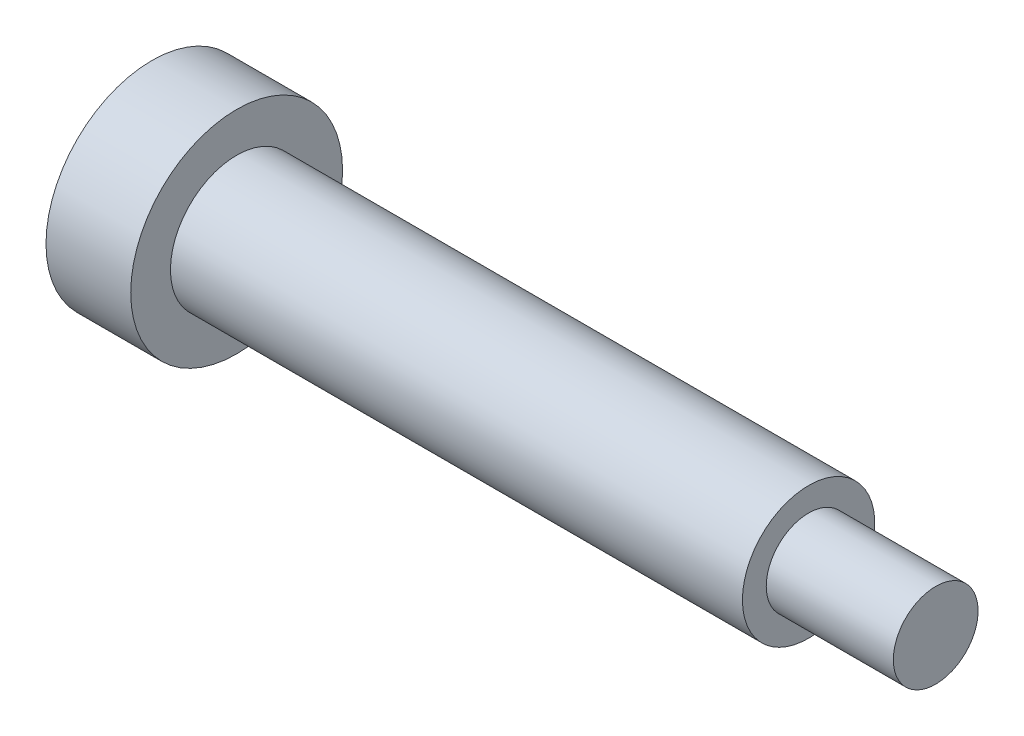
SolidWorks part; units mm, degrees
ref_plane "Front Plane" through (0, 0, 0) normal (0, 0, 1) x (1, 0, 0)
ref_plane "Top Plane" through (0, 0, 0) normal (0, 1, 0) x (1, 0, 0)
ref_plane "Right Plane" through (0, 0, 0) normal (1, 0, 0) x (0, 0, -1)
sketch "Sketch1" plane through (0, 0, 0) normal (0, 0, 1) x (1, 0, 0)
  line L0 (0, 0) -> (37, 0) construction
  line L1 (0, 0) -> (0, 5)
  line L2 (0, 5) -> (4, 5)
  line L3 (4, 5) -> (4, 3.125)
  line L4 (4, 3.125) -> (31, 3.125)
  line L5 (31, 3.125) -> (31, 2)
  line L6 (31, 2) -> (37, 2)
  line L7 (37, 2) -> (37, 0)
  line L8 (0, 0) -> (37, 0)
  point P5 (43.0511, 0.6767)
  dimension "D1" = 4
  dimension "D2" = 27
  dimension "D3" = 6
  dimension "D4" = 5
  dimension "D5" = 3.125
  dimension "D6" = 2
revolve "Revolve1" add sketch "Sketch1" angle 360 about L0
